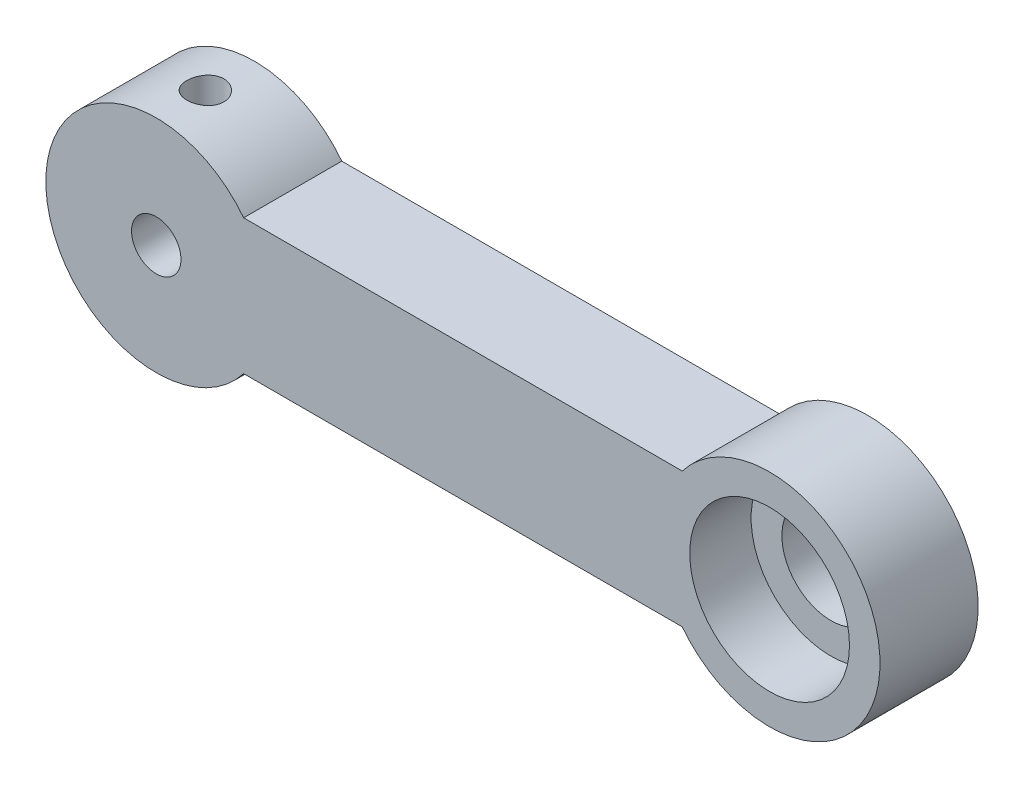
SolidWorks part; units mm, degrees
ref_plane "Front Plane" through (0, 0, 0) normal (0, 0, 1) x (1, 0, 0)
ref_plane "Top Plane" through (0, 0, 0) normal (0, 1, 0) x (1, 0, 0)
ref_plane "Right Plane" through (0, 0, 0) normal (1, 0, 0) x (0, 0, -1)
sketch "Sketch1" plane through (0, 0, 0) normal (0, 0, 1) x (1, 0, 0)
  line L1 (0, 0) -> (40, 0)
  line L2 (0, 0) -> (0, 11)
  line L3 (0, 11) -> (40, 11)
  arc A0 (40, 11) -> (40, 0) centre (47.1239, 5.5) cw
  dimension "D1" = 9
  dimension "D2" = 11
  dimension "D3" = 40
extrude "Boss-Extrude1" add sketch "Sketch1" along normal blind 8
sketch "Sketch3" plane through (0, 0, 8) normal (0, 0, 1) x (1, 0, 0)
  circle A0 centre (47.1239, 5.5) radius 4
  arc A1 (40, 0) -> (40, 11) centre (47.1239, 5.5) ccw construction
  dimension "D1" = 8
extrude "Cut-Extrude1" cut sketch "Sketch3" against normal through all
sketch "Sketch4" plane through (0, 0, 8) normal (0, 0, 1) x (1, 0, 0)
  circle A0 centre (47.1239, 5.5) radius 6.51
  dimension "D1" = 13.02
extrude "Cut-Extrude2" cut sketch "Sketch4" against normal blind 5
sketch "Sketch12" plane through (0, 0, 8) normal (0, 0, 1) x (1, 0, 0)
  line L0 (0, 0) -> (40, 0) construction
  circle A0 centre (-2.8761, 5.5) radius 9
  circle A1 centre (47.1239, 5.5) radius 4 construction
  dimension "D1" = 50
  dimension "D3" = 18
  dimension "D2" = 5.5
extrude "Boss-Extrude2" add sketch "Sketch12" against normal blind 8
sketch "Sketch13" plane through (0, 0, 8) normal (0, 0, 1) x (1, 0, 0)
  circle A0 centre (-2.8761, 5.5) radius 2.015
  dimension "D1" = 4.03
extrude "Cut-Extrude8" cut sketch "Sketch13" against normal through all
ref_plane "Plane1" through (0, 5.5, 0) normal (0, 1, 0) x (1, 0, 0)
sketch "Sketch14" plane through (0, 5.5, 0) normal (0, 1, 0) x (1, 0, 0)
  line L0 (-11.8761, 0) -> (-11.8761, -8) construction
  line L1 (4.2478, 0) -> (-11.8761, 0) construction
  circle A0 centre (-2.8761, -4) radius 1.51
  dimension "D1" = 3.02
  dimension "D2" = 9
  dimension "D3" = 4
extrude "Cut-Extrude10" cut sketch "Sketch14" against normal through all and the other way through all
